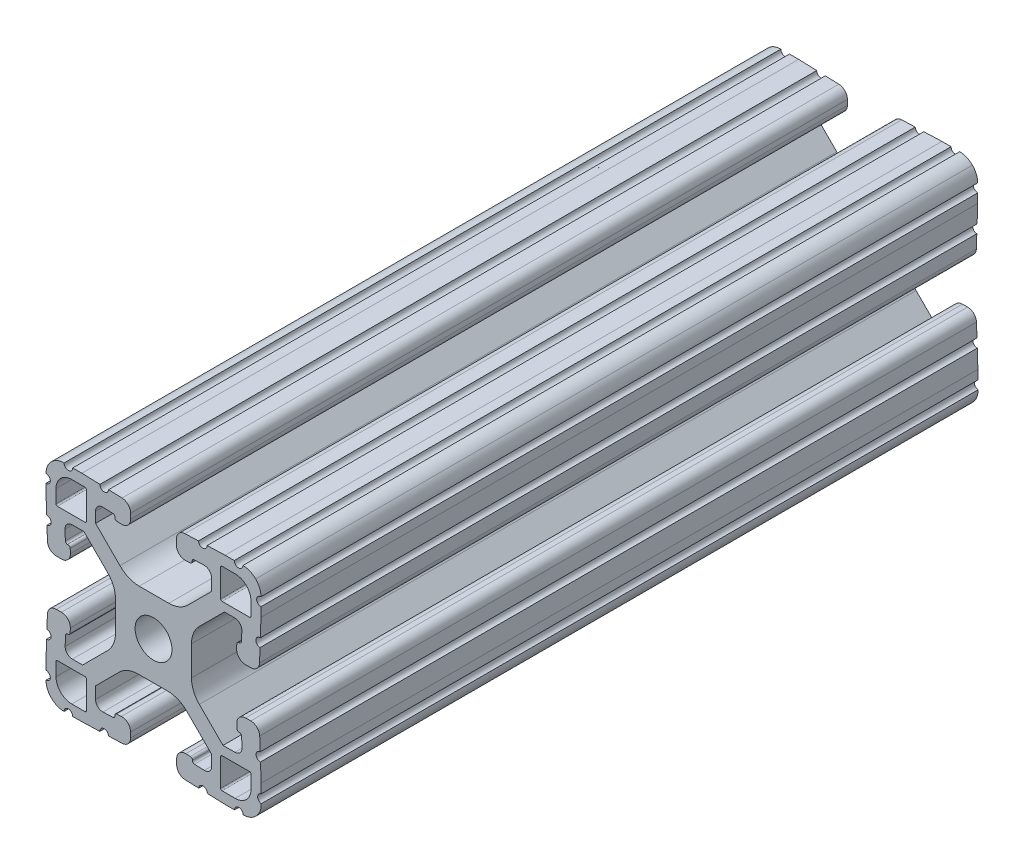
SolidWorks part; units mm, degrees
ref_plane "Front Plane" through (0, 0, 0) normal (0, 0, 1) x (1, 0, 0)
ref_plane "Top Plane" through (0, 0, 0) normal (0, 1, 0) x (1, 0, 0)
ref_plane "Right Plane" through (0, 0, 0) normal (1, 0, 0) x (0, 0, -1)
ref_plane "Plane1" through (0, 0, -25.4) normal (0, 0, -1) x (-1, 0, 0)
sketch "Sketch1" plane through (0, 0, -25.4) normal (0, 0, -1) x (-1, 0, 0)
  line L0 (-83.3577, 88.2941) -> (-83.3577, 93.1709)
  line L1 (-83.1037, 93.4249) -> (-80.767, 93.4249)
  line L2 (-77.9729, 90.6309) -> (-77.9729, 88.2941)
  line L3 (-78.2269, 88.0401) -> (-83.1037, 88.0401)
  line L4 (-83.3577, 59.2291) -> (-83.3577, 64.1059)
  line L5 (-83.1037, 64.3599) -> (-78.2269, 64.3599)
  line L6 (-77.9729, 64.1059) -> (-77.9729, 61.7691)
  line L7 (-80.767, 58.9751) -> (-83.1037, 58.9751)
  line L8 (-107.1423, 93.1709) -> (-107.1423, 88.2941)
  line L9 (-107.3963, 88.0401) -> (-112.2731, 88.0401)
  line L10 (-112.5271, 88.2941) -> (-112.5271, 90.6309)
  line L11 (-109.733, 93.4249) -> (-107.3963, 93.4249)
  line L12 (-107.1423, 64.1059) -> (-107.1423, 59.2291)
  line L13 (-107.3963, 58.9751) -> (-109.733, 58.9751)
  line L14 (-112.5271, 61.7691) -> (-112.5271, 64.1059)
  line L15 (-112.2731, 64.3599) -> (-107.3963, 64.3599)
  line L16 (-88.0437, 91.8626) -> (-86.2967, 91.9236)
  line L17 (-84.9824, 90.6544) -> (-84.9824, 88.8002)
  line L18 (-84.9824, 88.8002) -> (-89.3066, 84.476)
  line L19 (-92.7196, 83.0295) -> (-97.9616, 83.0295)
  line L20 (-101.3202, 84.4207) -> (-105.516, 88.6165)
  line L21 (-105.516, 88.6165) -> (-105.516, 90.7313)
  line L22 (-104.2017, 92.0006) -> (-102.4547, 91.9396)
  line L23 (-101.7262, 91.1059) -> (-100.9297, 91.0781)
  line L24 (-99.2999, 92.6519) -> (-99.2999, 93.5668)
  line L25 (-100.8197, 95.1407) -> (-103.2119, 95.2242)
  line L26 (-104.735, 95.2774) -> (-107.9359, 95.3892)
  line L27 (-107.9359, 95.3892) -> (-109.5615, 95.3892)
  line L28 (-114.2859, 90.6648) -> (-114.2859, 89.0392)
  line L29 (-114.2859, 89.0392) -> (-114.1741, 85.8383)
  line L30 (-114.1209, 84.3152) -> (-114.0374, 81.9231)
  line L31 (-112.4635, 80.4032) -> (-111.5486, 80.4032)
  line L32 (-109.9748, 82.033) -> (-110.0026, 82.8295)
  line L33 (-110.8377, 83.5577) -> (-110.8987, 85.3047)
  line L34 (-109.6294, 86.619) -> (-107.8072, 86.619)
  line L35 (-107.8072, 86.619) -> (-103.3649, 82.1768)
  line L36 (-101.9737, 78.8182) -> (-101.9737, 73.576)
  line L37 (-103.3649, 70.2174) -> (-107.5607, 66.0217)
  line L38 (-107.5607, 66.0217) -> (-109.6524, 66.0217)
  line L39 (-110.9217, 67.336) -> (-110.8607, 69.083)
  line L40 (-110.0322, 69.8124) -> (-110.0043, 70.6089)
  line L41 (-111.5782, 72.2387) -> (-112.4931, 72.2387)
  line L42 (-114.0669, 70.7189) -> (-114.1505, 68.3267)
  line L43 (-114.2036, 66.8036) -> (-114.3154, 63.6027)
  line L44 (-114.3154, 63.6027) -> (-114.3154, 61.9626)
  line L45 (-109.6111, 57.1437) -> (-107.9855, 57.1437)
  line L46 (-107.9855, 57.1437) -> (-104.7846, 57.2555)
  line L47 (-103.2615, 57.3086) -> (-100.8694, 57.3922)
  line L48 (-99.3495, 58.966) -> (-99.3495, 59.8809)
  line L49 (-100.9794, 61.4548) -> (-101.7758, 61.4269)
  line L50 (-102.5054, 60.599) -> (-104.2524, 60.538)
  line L51 (-105.5667, 61.8072) -> (-105.5667, 63.6295)
  line L52 (-105.5667, 63.6295) -> (-101.1311, 68.065)
  line L53 (-97.7725, 69.4562) -> (-92.5304, 69.4562)
  line L54 (-89.1717, 68.065) -> (-84.976, 63.8692)
  line L55 (-84.976, 63.8692) -> (-84.976, 61.7811)
  line L56 (-86.2903, 60.5118) -> (-88.0373, 60.5728)
  line L57 (-88.7596, 61.4332) -> (-89.5561, 61.461)
  line L58 (-91.1859, 59.8872) -> (-91.1859, 58.9723)
  line L59 (-89.6661, 57.3985) -> (-87.2739, 57.3149)
  line L60 (-85.7508, 57.2617) -> (-82.5499, 57.15)
  line L61 (-82.5499, 57.15) -> (-80.9244, 57.15)
  line L62 (-76.2, 61.8744) -> (-76.2, 63.4999)
  line L63 (-76.2, 63.4999) -> (-76.3117, 66.7008)
  line L64 (-76.3649, 68.2239) -> (-76.4484, 70.6161)
  line L65 (-78.0223, 72.1359) -> (-78.9372, 72.1359)
  line L66 (-80.511, 70.5061) -> (-80.4832, 69.7096)
  line L67 (-79.6552, 68.9801) -> (-79.5942, 67.2331)
  line L68 (-80.8634, 65.9188) -> (-82.6857, 65.9188)
  line L69 (-82.6857, 65.9188) -> (-87.1213, 70.3543)
  line L70 (-88.5125, 73.7128) -> (-88.5126, 78.955)
  line L71 (-87.1214, 82.3137) -> (-82.9257, 86.5095)
  line L72 (-82.9257, 86.5095) -> (-80.8375, 86.5095)
  line L73 (-79.5682, 85.1951) -> (-79.6293, 83.4482)
  line L74 (-80.4896, 82.7258) -> (-80.5175, 81.9294)
  line L75 (-78.9436, 80.2995) -> (-78.0287, 80.2995)
  line L76 (-76.4549, 81.8194) -> (-76.3713, 84.2115)
  line L77 (-76.3182, 85.7346) -> (-76.2064, 88.9355)
  line L78 (-76.2064, 88.9355) -> (-76.2064, 90.5611)
  line L79 (-80.9308, 95.2855) -> (-82.5564, 95.2855)
  line L80 (-82.5564, 95.2855) -> (-85.7573, 95.1737)
  line L81 (-87.2803, 95.1205) -> (-89.6725, 95.037)
  line L82 (-91.1924, 93.4632) -> (-91.1924, 92.5483)
  line L83 (-89.5625, 90.9744) -> (-88.7661, 91.0023)
  arc A0 (-83.3577, 93.1709) -> (-83.1037, 93.4249) centre (-83.1037, 93.1709) cw
  arc A1 (-80.767, 93.4249) -> (-77.9729, 90.6309) centre (-80.7669, 90.6309) cw
  arc A2 (-77.9729, 88.2941) -> (-78.2269, 88.0401) centre (-78.2269, 88.2941) cw
  arc A3 (-83.1037, 88.0401) -> (-83.3577, 88.2941) centre (-83.1037, 88.2941) cw
  arc A4 (-83.1037, 58.9751) -> (-83.3577, 59.2291) centre (-83.1037, 59.2291) cw
  arc A5 (-83.3577, 64.1059) -> (-83.1037, 64.3599) centre (-83.1037, 64.1059) cw
  arc A6 (-78.2269, 64.3599) -> (-77.9729, 64.1059) centre (-78.2269, 64.1059) cw
  arc A7 (-77.9729, 61.7691) -> (-80.767, 58.9751) centre (-80.7669, 61.7691) cw
  arc A8 (-107.3963, 93.4249) -> (-107.1423, 93.1709) centre (-107.3963, 93.1709) cw
  arc A9 (-107.1423, 88.2941) -> (-107.3963, 88.0401) centre (-107.3963, 88.2941) cw
  arc A10 (-112.2731, 88.0401) -> (-112.5271, 88.2941) centre (-112.2731, 88.2941) cw
  arc A11 (-112.5271, 90.6309) -> (-109.733, 93.4249) centre (-109.7331, 90.6309) cw
  arc A12 (-107.1423, 59.2291) -> (-107.3963, 58.9751) centre (-107.3963, 59.2291) cw
  arc A13 (-109.733, 58.9751) -> (-112.5271, 61.7691) centre (-109.7331, 61.7691) cw
  arc A14 (-112.5271, 64.1059) -> (-112.2731, 64.3599) centre (-112.2731, 64.1059) cw
  arc A15 (-107.3963, 64.3599) -> (-107.1423, 64.1059) centre (-107.3963, 64.1059) cw
  circle A16 centre (-95.25, 76.2) radius 3.2639
  arc A17 (-88.7661, 91.0023) -> (-88.3984, 91.383) centre (-88.7794, 91.383) ccw
  arc A18 (-88.3984, 91.383) -> (-88.0437, 91.8626) centre (-88.0304, 91.4819) cw
  arc A19 (-86.2967, 91.9236) -> (-84.9824, 90.6544) centre (-86.2524, 90.6544) cw
  arc A20 (-89.3066, 84.476) -> (-92.7196, 83.0295) centre (-92.7196, 87.7793) cw
  arc A21 (-97.9616, 83.0295) -> (-101.3202, 84.4207) centre (-97.9616, 87.7793) cw
  arc A22 (-105.516, 90.7313) -> (-104.2017, 92.0006) centre (-104.246, 90.7313) cw
  arc A23 (-102.4547, 91.9396) -> (-102.087, 91.5588) centre (-102.468, 91.5588) cw
  arc A24 (-102.087, 91.5588) -> (-101.7262, 91.1059) centre (-101.7129, 91.4867) ccw
  arc A25 (-100.9297, 91.0781) -> (-99.2999, 92.6519) centre (-100.8747, 92.6519) ccw
  arc A26 (-99.2999, 93.5668) -> (-100.8197, 95.1407) centre (-100.8747, 93.5668) ccw
  arc A27 (-103.2119, 95.2242) -> (-104.735, 95.2774) centre (-103.9735, 95.2508) cw
  arc A28 (-109.5615, 95.3892) -> (-111.0855, 95.3892) centre (-110.3235, 95.3892) cw
  arc A29 (-111.0855, 95.3892) -> (-113.3432, 94.4465) centre (-111.0855, 92.2142) ccw
  arc A30 (-113.3432, 94.4465) -> (-114.2859, 92.1888) centre (-111.1109, 92.1888) ccw
  arc A31 (-114.2859, 92.1888) -> (-114.2859, 90.6648) centre (-114.2859, 91.4268) cw
  arc A32 (-114.1741, 85.8383) -> (-114.1209, 84.3152) centre (-114.1475, 85.0768) cw
  arc A33 (-114.0374, 81.9231) -> (-112.4635, 80.4032) centre (-112.4635, 81.978) ccw
  arc A34 (-111.5486, 80.4032) -> (-109.9748, 82.033) centre (-111.5486, 81.978) ccw
  arc A35 (-110.0026, 82.8295) -> (-110.3834, 83.1972) centre (-110.3834, 82.8162) ccw
  arc A36 (-110.3834, 83.1972) -> (-110.8377, 83.5577) centre (-110.4569, 83.571) cw
  arc A37 (-110.8987, 85.3047) -> (-109.6294, 86.619) centre (-109.6294, 85.349) cw
  arc A38 (-103.3649, 82.1768) -> (-101.9737, 78.8182) centre (-106.7235, 78.8182) cw
  arc A39 (-101.9737, 73.576) -> (-103.3649, 70.2174) centre (-106.7235, 73.576) cw
  arc A40 (-109.6524, 66.0217) -> (-110.9217, 67.336) centre (-109.6524, 67.2917) cw
  arc A41 (-110.8607, 69.083) -> (-110.4799, 69.4507) centre (-110.4799, 69.0697) cw
  arc A42 (-110.4799, 69.4507) -> (-110.0322, 69.8124) centre (-110.413, 69.8257) ccw
  arc A43 (-110.0043, 70.6089) -> (-111.5782, 72.2387) centre (-111.5782, 70.6639) ccw
  arc A44 (-112.4931, 72.2387) -> (-114.0669, 70.7189) centre (-112.4931, 70.6639) ccw
  arc A45 (-114.1505, 68.3267) -> (-114.2036, 66.8036) centre (-114.1771, 67.5652) cw
  arc A46 (-114.3154, 61.9626) -> (-114.3332, 60.4644) centre (-114.4639, 61.2152) cw
  arc A47 (-114.3332, 60.4644) -> (-113.3928, 58.0864) centre (-111.1605, 60.3441) ccw
  arc A48 (-113.3928, 58.0864) -> (-111.1351, 57.1437) centre (-111.1351, 60.3187) ccw
  arc A49 (-111.1351, 57.1437) -> (-109.6111, 57.1437) centre (-110.3731, 57.1437) cw
  arc A50 (-104.7846, 57.2555) -> (-103.2615, 57.3086) centre (-104.0231, 57.2821) cw
  arc A51 (-100.8694, 57.3922) -> (-99.3495, 58.966) centre (-100.9243, 58.966) ccw
  arc A52 (-99.3495, 59.8809) -> (-100.9794, 61.4548) centre (-100.9243, 59.8809) ccw
  arc A53 (-101.7758, 61.4269) -> (-102.1435, 61.0462) centre (-101.7625, 61.0462) ccw
  arc A54 (-102.1435, 61.0462) -> (-102.5054, 60.599) centre (-102.5187, 60.9797) cw
  arc A55 (-104.2524, 60.538) -> (-105.5667, 61.8072) centre (-104.2967, 61.8072) cw
  arc A56 (-101.1311, 68.065) -> (-97.7725, 69.4562) centre (-97.7725, 64.7064) cw
  arc A57 (-92.5304, 69.4562) -> (-89.1717, 68.065) centre (-92.5304, 64.7064) cw
  arc A58 (-84.976, 61.7811) -> (-86.2903, 60.5118) centre (-86.246, 61.7811) cw
  arc A59 (-88.0373, 60.5728) -> (-88.405, 60.9536) centre (-88.024, 60.9536) cw
  arc A60 (-88.405, 60.9536) -> (-88.7596, 61.4332) centre (-88.7729, 61.0524) ccw
  arc A61 (-89.5561, 61.461) -> (-91.1859, 59.8872) centre (-89.6111, 59.8872) ccw
  arc A62 (-91.1859, 58.9723) -> (-89.6661, 57.3985) centre (-89.6111, 58.9723) ccw
  arc A63 (-87.2739, 57.3149) -> (-85.7508, 57.2617) centre (-86.5124, 57.2883) cw
  arc A64 (-80.9244, 57.15) -> (-79.4004, 57.15) centre (-80.1624, 57.15) cw
  arc A65 (-79.4004, 57.15) -> (-77.1426, 58.0927) centre (-79.4004, 60.325) ccw
  arc A66 (-77.1426, 58.0927) -> (-76.2, 60.3504) centre (-79.375, 60.3504) ccw
  arc A67 (-76.2, 60.3504) -> (-76.2, 61.8744) centre (-76.2, 61.1124) cw
  arc A68 (-76.3117, 66.7008) -> (-76.3649, 68.2239) centre (-76.3383, 67.4624) cw
  arc A69 (-76.4484, 70.6161) -> (-78.0223, 72.1359) centre (-78.0223, 70.5611) ccw
  arc A70 (-78.9372, 72.1359) -> (-80.511, 70.5061) centre (-78.9372, 70.5611) ccw
  arc A71 (-80.4832, 69.7096) -> (-80.1024, 69.342) centre (-80.1024, 69.723) ccw
  arc A72 (-80.1024, 69.342) -> (-79.6552, 68.9801) centre (-80.036, 68.9668) cw
  arc A73 (-79.5942, 67.2331) -> (-80.8634, 65.9188) centre (-80.8634, 67.1888) cw
  arc A74 (-87.1213, 70.3543) -> (-88.5125, 73.7128) centre (-83.7627, 73.7129) cw
  arc A75 (-88.5126, 78.955) -> (-87.1214, 82.3137) centre (-83.7628, 78.9551) cw
  arc A76 (-80.8375, 86.5095) -> (-79.5682, 85.1951) centre (-80.8375, 85.2395) cw
  arc A77 (-79.6293, 83.4482) -> (-80.01, 83.0805) centre (-80.01, 83.4615) cw
  arc A78 (-80.01, 83.0805) -> (-80.4896, 82.7258) centre (-80.1089, 82.7125) ccw
  arc A79 (-80.5175, 81.9294) -> (-78.9436, 80.2995) centre (-78.9436, 81.8743) ccw
  arc A80 (-78.0287, 80.2995) -> (-76.4549, 81.8194) centre (-78.0287, 81.8743) ccw
  arc A81 (-76.3713, 84.2115) -> (-76.3182, 85.7346) centre (-76.3448, 84.9731) cw
  arc A82 (-76.2064, 90.5611) -> (-76.2064, 92.0851) centre (-76.2064, 91.3231) cw
  arc A83 (-76.2064, 92.0851) -> (-77.1491, 94.3428) centre (-79.3814, 92.0851) ccw
  arc A84 (-77.1491, 94.3428) -> (-79.4068, 95.2855) centre (-79.4068, 92.1105) ccw
  arc A85 (-79.4068, 95.2855) -> (-80.9308, 95.2855) centre (-80.1688, 95.2855) cw
  arc A86 (-85.7573, 95.1737) -> (-87.2803, 95.1205) centre (-86.5188, 95.1471) cw
  arc A87 (-89.6725, 95.037) -> (-91.1924, 93.4632) centre (-89.6176, 93.4632) ccw
  arc A88 (-91.1924, 92.5483) -> (-89.5625, 90.9744) centre (-89.6176, 92.5483) ccw
extrude "Boss-Extrude1" add sketch "Sketch1" against normal blind 127
